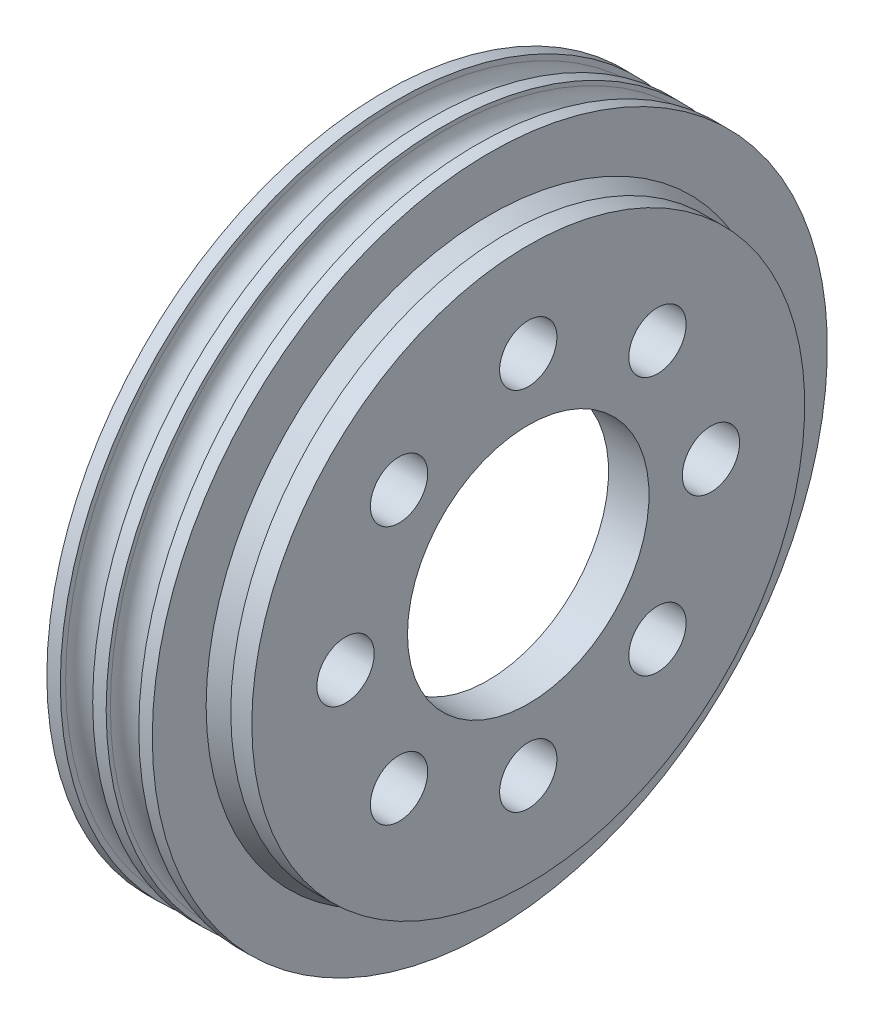
SolidWorks part; units mm, degrees
ref_plane "Front Plane" through (0, 0, 0) normal (0, 0, 1) x (1, 0, 0)
ref_plane "Top Plane" through (0, 0, 0) normal (0, 1, 0) x (1, 0, 0)
ref_plane "Right Plane" through (0, 0, 0) normal (1, 0, 0) x (0, 0, -1)
sketch "Sketch1" plane through (0, 0, 0) normal (0, 0, 1) x (1, 0, 0)
  line L0 (1.2561, 4.8317) -> (1.2561, -3.1566)
  line L1 (-14.4439, -1.3284) -> (0.9561, -9.2302)
  line L2 (0.9561, -27.3183) -> (6.9561, -27.3183)
  line L3 (1.2561, -3.1566) -> (3.8359, -4.2302)
  line L4 (0.9561, -27.3183) -> (0.9561, -9.2302)
  line L5 (-14.4439, 4.7698) -> (-12.4439, 4.7698)
  line L6 (-0.7439, 4.8317) -> (-0.7439, 4.1504)
  line L7 (-7.6439, 3.9838) -> (-7.6439, 4.7698)
  line L8 (-5.6439, 4.1504) -> (-5.6439, 4.7698)
  line L9 (-7.6439, 4.7698) -> (-5.6439, 4.7698)
  line L10 (-14.4439, 4.7698) -> (-14.4439, -1.3284)
  line L11 (-12.4439, 4.7698) -> (-12.4439, 3.9838)
  line L12 (-0.7439, 4.8317) -> (1.2561, 4.8317)
  line L13 (-24.7572, -45.2302) -> (67.289, -45.2302) construction
  line L14 (3.8359, -4.2302) -> (6.9561, -4.2302)
  line L16 (6.9561, -27.3183) -> (6.9561, -4.2302)
  arc A0 (-5.6439, 4.1504) -> (-0.7439, 4.1504) centre (-3.1939, 4.1504) ccw
  arc A1 (-7.6439, 3.9838) -> (-12.4439, 3.9838) centre (-10.0439, 3.9838) cw
  point P47 (-14.4439, -1.3284)
  dimension "D6" = 2
  dimension "D10" = 4.8
  dimension "D2" = 50
  dimension "D12" = 6
  dimension "D1" = 21.4
  dimension "D3" = 36
  dimension "D4" = 17.9119
  dimension "D5" = 15.7
  dimension "D8" = 2
  dimension "D9" = 2
  dimension "D11" = 41
revolve "Revolve1" add sketch "Sketch1" angle 360 about L13
sketch "Sketch2" plane through (0.9561, 0, 0) normal (-1, 0, 0) x (0, 0, 1)
  circle A1 centre (0, -18.1302) radius 4.25
  circle A2 centre (19.1626, -26.0676) radius 4.25
  circle A3 centre (27.1, -45.2302) radius 4.25
  circle A4 centre (19.1626, -64.3928) radius 4.25
  circle A5 centre (0, -72.3302) radius 4.25
  circle A6 centre (-19.1626, -64.3928) radius 4.25
  circle A7 centre (-27.1, -45.2302) radius 4.25
  circle A8 centre (-19.1626, -26.0676) radius 4.25
  dimension "D2" = 8.5
extrude "Cut-Extrude1" cut sketch "Sketch2" against normal blind 10
